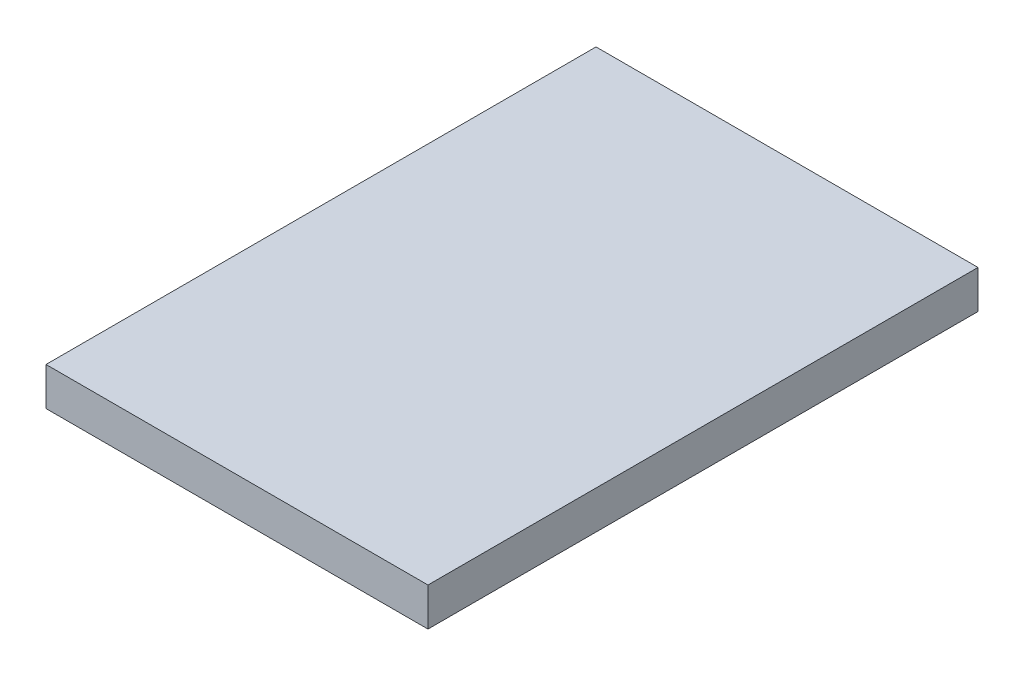
SolidWorks part; units mm, degrees
ref_plane "Front" through (0, 0, 0) normal (0, 0, 1) x (1, 0, 0)
ref_plane "Top" through (0, 0, 0) normal (0, 1, 0) x (1, 0, 0)
ref_plane "Right" through (0, 0, 0) normal (1, 0, 0) x (0, 0, -1)
sketch "Sketch1" plane through (0, 0, 0) normal (0, 1, 0) x (1, 0, 0)
  line L1 (0, 0) -> (50, 0)
  line L2 (0, 0) -> (0, 72)
  line L3 (0, 72) -> (50, 72)
  line L4 (50, 0) -> (50, 72)
  dimension "D1" = 72
  dimension "D2" = 50
extrude "Boss-Extrude1" add sketch "Sketch1" along normal blind 5
